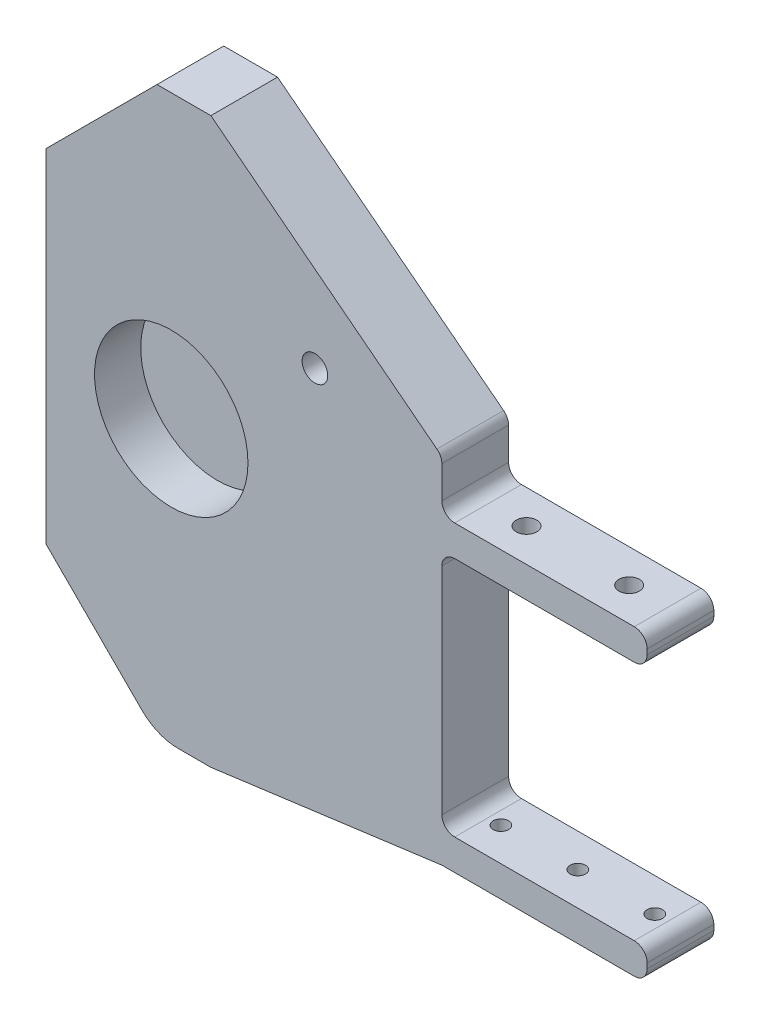
SolidWorks part; units mm, degrees
material "5052-H36"
ref_plane "Plano frontal" through (0, 0, 0) normal (0, 0, 1) x (1, 0, 0)
ref_plane "Plano superior" through (0, 0, 0) normal (0, 1, 0) x (1, 0, 0)
ref_plane "Plano direito" through (0, 0, 0) normal (1, 0, 0) x (0, 0, -1)
sketch "Esboço1" plane through (0, 0, 0) normal (0, 0, 1) x (1, 0, 0)
  line L0 (79.1281, 0) -> (0, 0) construction
  line L3 (4.9801, 55) -> (32.742, 55)
  line L6 (32.742, 55) -> (-22.7817, 55)
  line L12 (-22.7817, 55) -> (-44.3754, 33.4063)
  line L14 (-44.3754, -33.4063) -> (-22.7817, -55)
  line L15 (-22.7817, -55) -> (32.742, -55)
  line L18 (393.8557, 316.0739) -> (396.402, 318.6203) [skipped]
  line L19 (55, 501.996) -> (55, 520.8093) [skipped]
  line L20 (-316.0739, 393.8557) -> (-318.6203, 396.402) [skipped]
  line L21 (32.742, 55) -> (32.742, 10)
  line L22 (32.742, -49) -> (32.742, -55)
  line L23 (32.742, -49) -> (72.742, -49)
  line L25 (32.742, -43) -> (72.742, -43)
  line L26 (72.742, -49) -> (72.742, -43)
  line L27 (32.742, 4) -> (32.742, -43)
  line L28 (32.742, 4) -> (72.742, 4)
  line L30 (32.742, 10) -> (72.742, 10)
  line L31 (72.742, 4) -> (72.742, 10)
  line L32 (-44.3754, 33.4063) -> (-44.3754, -33.4063)
  line L34 (-55, 7.7563) -> (-55, -6.3461) [skipped]
  circle A0 centre (0, 0) radius 15 construction
  arc A3 (4.9801, 55) -> (0, -55.225) centre (0, 0) ccw construction
  point P14 (4.9801, 55)
  dimension "D1" = 30
  dimension "D5" = 110
  dimension "D6" = 40
  dimension "D7" = 6
  dimension "D8" = 6
  dimension "D9" = 45
extrude "Ressalto-extrusão1" add sketch "Esboço1" along normal mid plane 13
sketch "Esboço2" plane through (0, 0, 6.5) normal (0, 0, 1) x (1, 0, 0)
  circle A1 centre (-20, 0) radius 14.95
  dimension "D1" = 29.9
  dimension "D2" = 20
extrude "Corte-extrusão1" cut sketch "Esboço2" against normal blind 9
sketch "Esboço3" plane through (0, 0, 6.5) normal (0, 0, 1) x (1, 0, 0)
  line L0 (-22.7817, -55) -> (32.742, -55) construction
  line L1 (-12.2817, -55) -> (32.742, -49)
  line L2 (32.742, -49) -> (32.742, -55)
  line L3 (32.742, -55) -> (-12.2817, -55)
  line L4 (-12.2817, -55) -> (-12.2817, 66.3095) construction
  line L6 (32.742, 10) -> (72.742, 10) construction
  line L11 (32.742, 55) -> (-12.2817, 55)
  line L12 (-12.2817, 55) -> (32.742, 20)
  line L13 (32.742, 20) -> (32.742, 55)
  circle A0 centre (8, 22.5) radius 2.5
  point P0 (-12.2817, -55)
  dimension "D2" = 5
  dimension "D1" = 10.5
  dimension "D3" = 22.5
  dimension "D4" = 28
  dimension "D5" = 10
extrude "Corte-extrusão2" cut sketch "Esboço3" against normal blind 13
fillet "Filete1" radius 10 1 edges at (-22.7817, -55, 0)
sketch "Esboço4" plane through (0, 0, -6.5) normal (0, 0, -1) x (-1, 0, 0)
  line L0 (44.3754, 33.4063) -> (44.3754, -33.4063) construction
  circle A0 centre (36.3754, 8.4063) radius 2
  circle A1 centre (12.9554, -16.5937) radius 2
  circle A2 centre (22.3754, -27.5937) radius 2
  dimension "D1" = 4
  dimension "D2" = 25
  dimension "D3" = 8
  dimension "D4" = 23.42
  dimension "D5" = 25
  dimension "D6" = 36
  dimension "D7" = 14
extrude "Corte-extrusão3" cut sketch "Esboço4" against normal blind 10
sketch "Esboço6" plane through (0, 10, 0) normal (0, 1, 0) x (1, 0, 0)
  line L0 (32.742, -6.5) -> (72.742, -6.5) construction
  circle A0 centre (42.742, -0.0016) radius 2
  circle A1 centre (62.742, -0.0016) radius 2
  circle A2 centre (42.742, -0.0016) radius 2 construction
  dimension "D1" = 20
  dimension "D2" = 6.4984
extrude "Corte-extrusão4" cut sketch "Esboço6" against normal blind 10
sketch "Esboço7" plane through (0, -49, 0) normal (0, -1, 0) x (1, 0, 0)
  line L0 (32.742, -6.5) -> (72.742, -6.5) construction
  line L1 (37.742, 0) -> (67.742, 0) construction
  line L2 (72.742, 6.5) -> (72.742, -6.5) construction
  circle A0 centre (37.742, 0) radius 1.5
  circle A1 centre (52.742, 0) radius 1.5
  circle A2 centre (67.742, 0) radius 1.5
  dimension "D1" = 3
  dimension "D2" = 6.5
  dimension "D3" = 5
  dimension "D4" = 20
  dimension "D5" = 35
extrude "Corte-extrusão5" cut sketch "Esboço7" against normal blind 10
fillet "Filete2" radius 2.5 8 edges at (72.742, -49, 0) (72.742, -43, 0) (72.742, 4, 0) (72.742, 10, 0) (32.742, 20, 0) (32.742, -43, 0) (32.742, 10, 0) (32.742, 4, 0)
